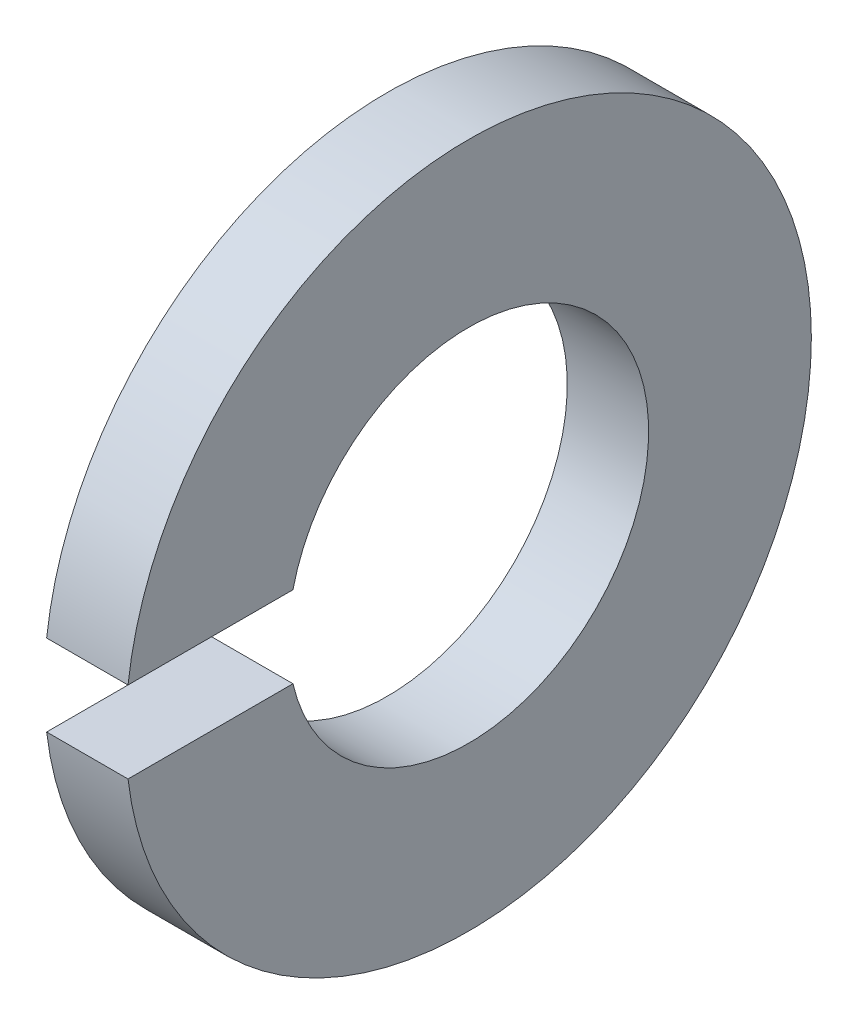
SolidWorks part; units mm, degrees
material "ステンレス"
ref_plane "Front Plane" through (0, 0, 0) normal (0, 0, 1) x (1, 0, 0)
ref_plane "Top Plane" through (0, 0, 0) normal (0, 1, 0) x (1, 0, 0)
ref_plane "Right Plane" through (0, 0, 0) normal (1, 0, 0) x (0, 0, -1)
sketch "Sketch1" plane through (0, 0, 0) normal (0, 0, 1) x (1, 0, 0)
  line L0 (-0.7, 0) -> (0, 0) construction
  line L2 (0, 2.95) -> (-0.7, 2.95)
  line L3 (0, 2.95) -> (0, 1.55)
  line L4 (0, 1.55) -> (-0.7, 1.55)
  line L5 (-0.7, 2.95) -> (-0.7, 1.55)
  dimension "D" = 5.9
  dimension "D_s" = 3.1
  dimension "T_s" = 0.7
revolve "Revolve1" add sketch "Sketch1" angle 360 about L0
sketch "Sketch2" plane through (0, 0, 0) normal (1, 0, 0) x (0, 0, -1)
  line L0 (-1.51, -0.35) -> (-2.9292, -0.35)
  line L1 (-1.51, 0.35) -> (-2.9292, 0.35)
  line L2 (-3.5019, 0) -> (0.1994, 0) construction
  circle A0 centre (0, 0) radius 2.95 construction
  circle A1 centre (0, 0) radius 1.55 construction
  arc A2 (-2.9292, 0.35) -> (-2.9292, -0.35) centre (0, 0) ccw
  arc A3 (-1.51, 0.35) -> (-1.51, -0.35) centre (0, 0) ccw
  dimension "MSM_1" = 0.7
extrude "Cut-Extrude1" cut sketch "Sketch2" against normal through all
